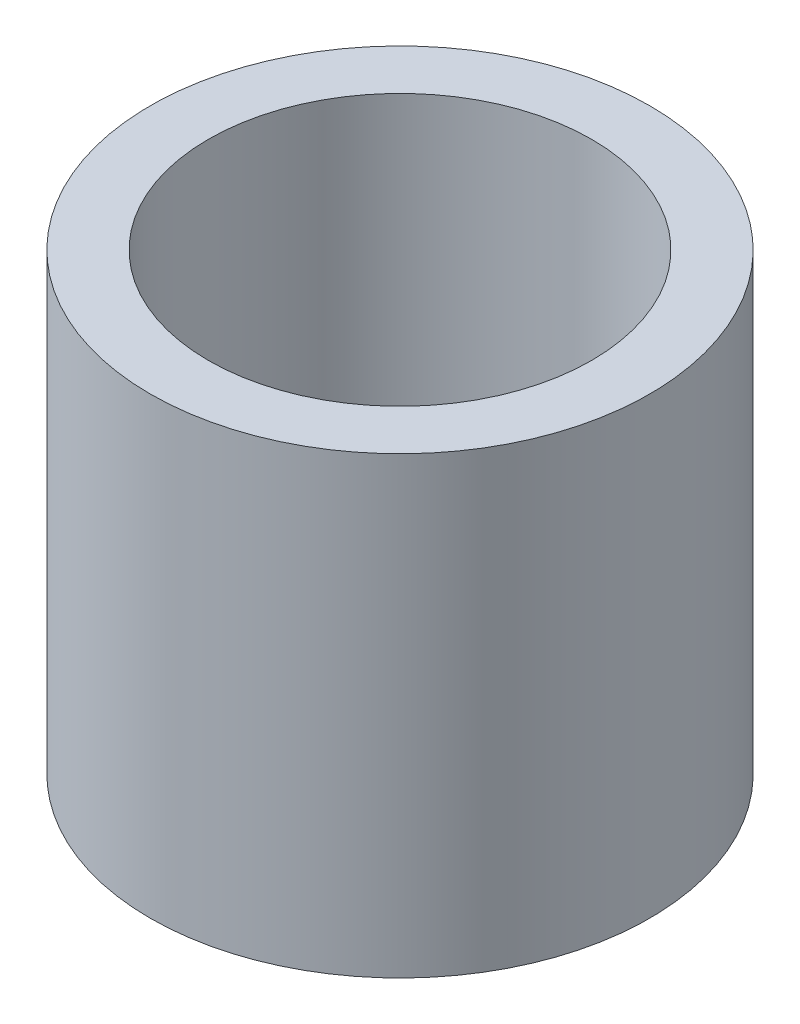
SolidWorks part; units mm, degrees
ref_plane "Front Plane" through (0, 0, 0) normal (0, 0, 1) x (1, 0, 0)
ref_plane "Top Plane" through (0, 0, 0) normal (0, 1, 0) x (1, 0, 0)
ref_plane "Right Plane" through (0, 0, 0) normal (1, 0, 0) x (0, 0, -1)
sketch "Sketch1" plane through (0, 0, 0) normal (0, 0, 1) x (1, 0, 0)
  line L0 (13.3985, 31.75) -> (13.3985, 4.318)
  line L1 (13.3985, 4.318) -> (0, 4.318)
  line L2 (0, -55) -> (0, 55) construction
  line L3 (0, 4.318) -> (0, 0)
  line L4 (0, 0) -> (17.4625, 0)
  line L5 (55, 0) -> (-55, 0) construction
  line L6 (17.4625, 0) -> (17.4625, 31.75)
  line L7 (17.4625, 31.75) -> (13.3985, 31.75)
  dimension "D1" = 17.4625
  dimension "D2" = 4.064
  dimension "D3" = 31.75
  dimension "D4" = 27.432
revolve "Revolve1" add sketch "Sketch1" angle 360 about L3
hole_wizard "#6 Clearance Hole1" positions "Sketch3" profile "Sketch4" hole size "#6" standard "ANSI Inch" end condition through all
sketch "Sketch3" plane through (0, 0, 0) normal (0, -1, 0) x (-1, 0, 0)
  point P0 (0, 0)
sketch "Sketch4" plane through (0, 0, 0) normal (1, 0, 0) x (0, 0, -1)
  line L0 (0, 0) -> (0, 31.75)
  line L1 (0, 31.75) -> (1.8986, 31.75)
  line L2 (1.8986, 31.75) -> (1.8986, 0)
  line L5 (1.8986, 0) -> (0, 0)
  line L11 (0, -6.35) -> (0, 107.95) construction
  dimension "Thru Hole Dia." = 3.7973
  dimension "Thru Hole Depth" = 31.75
